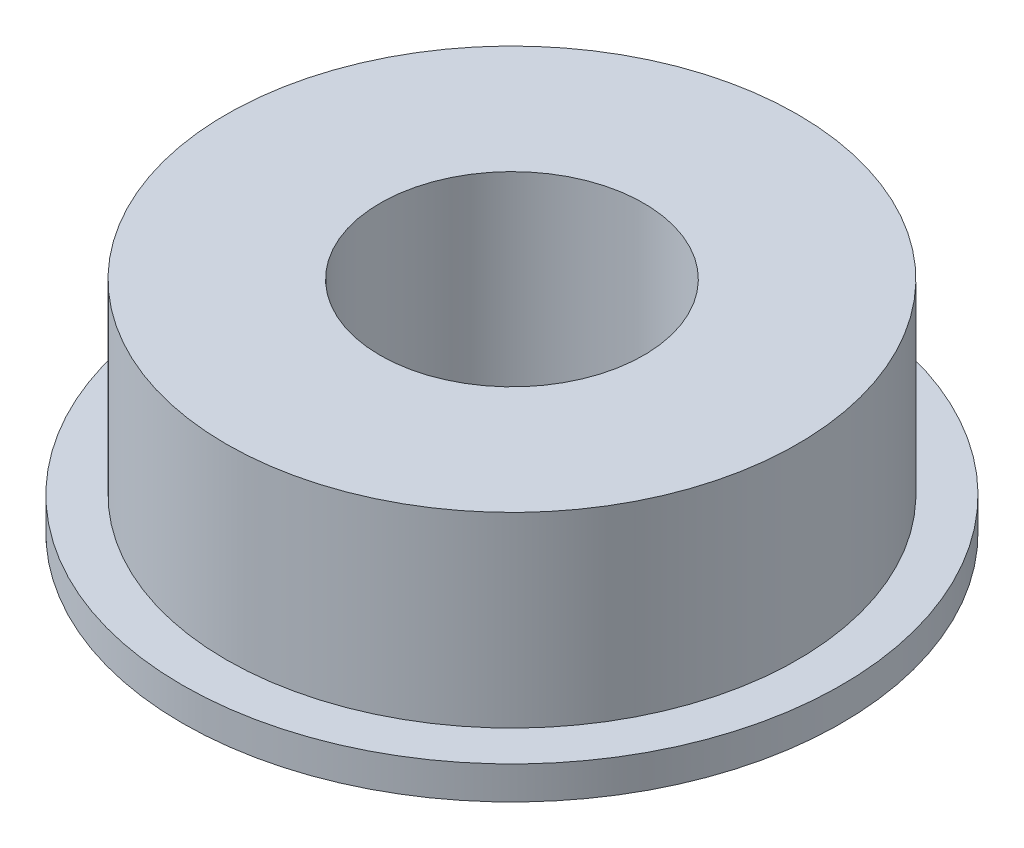
SolidWorks part; units mm, degrees
material "Cast Alloy Steel"
ref_plane "Front Plane" through (0, 0, 0) normal (0, 0, 1) x (1, 0, 0)
ref_plane "Top Plane" through (0, 0, 0) normal (0, 1, 0) x (1, 0, 0)
ref_plane "Right Plane" through (0, 0, 0) normal (1, 0, 0) x (0, 0, -1)
sketch "Sketch1" plane through (0, 0, 0) normal (0, 0, 1) x (1, 0, 0)
  line L0 (3, 0) -> (7.5, 0)
  line L1 (7.5, 0) -> (7.5, 0.75)
  line L2 (7.5, 0.75) -> (6.5, 0.75)
  line L3 (6.5, 0.75) -> (6.5, 5)
  line L4 (6.5, 5) -> (3, 5)
  line L5 (3, 5) -> (3, 0)
  line L6 (3, 0) -> (0, 0) construction
  dimension "D1" = 3
  dimension "D2" = 6.5
  dimension "D3" = 7.5
  dimension "D4" = 5
  dimension "D5" = 0.75
ref_axis "Axis1" through (0, 133.35, 0) along (0, -1, 0)
revolve "Revolve1" add sketch "Sketch1" angle 360 about axis through (0, 133.35, 0) along (0, -1, 0)
